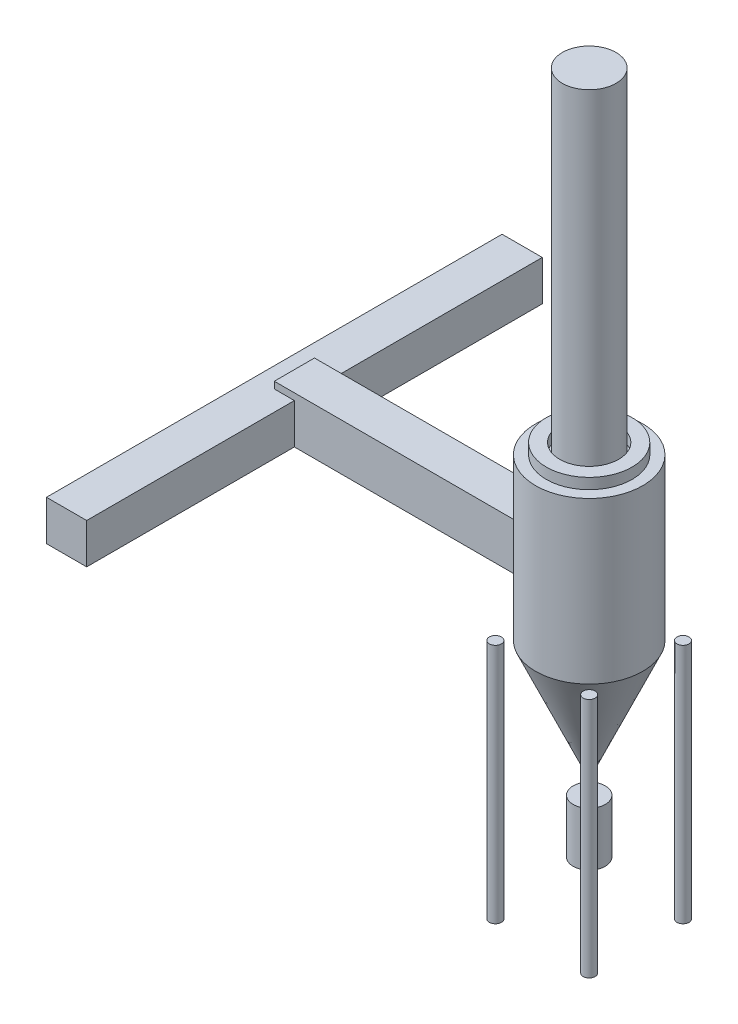
SolidWorks part; units mm, degrees
ref_plane "Front Plane" through (0, 0, 0) normal (0, 0, 1) x (1, 0, 0)
ref_plane "Top Plane" through (0, 0, 0) normal (0, 1, 0) x (1, 0, 0)
ref_plane "Right Plane" through (0, 0, 0) normal (1, 0, 0) x (0, 0, -1)
other "Configuration Table"
sketch "Sketch1" plane through (0, 0, 0) normal (0, 1, 0) x (1, 0, 0)
  circle A0 centre (1850, 5150) radius 45
extrude "Boss-Extrude1" add sketch "Sketch1" along normal blind 1800
sketch "Sketch2" plane through (0, 0, 0) normal (0, 1, 0) x (1, 0, 0)
  circle A0 centre (2550, 5150) radius 45
extrude "Boss-Extrude2" add sketch "Sketch2" along normal blind 1800
sketch "Sketch3" plane through (0, 0, 0) normal (0, 1, 0) x (1, 0, 0)
  circle A0 centre (1850, 5850) radius 45
extrude "Boss-Extrude3" add sketch "Sketch3" along normal blind 1800
sketch "Sketch4" plane through (0, 0, 0) normal (0, 1, 0) x (1, 0, 0)
  circle A0 centre (2550, 5850) radius 45
extrude "Boss-Extrude4" add sketch "Sketch4" along normal blind 1800
sketch "Sketch5" plane through (0, 0, 0) normal (0, 1, 0) x (1, 0, 0)
  circle A0 centre (2200, 5500) radius 120
extrude "Boss-Extrude5" add sketch "Sketch5" along normal blind 400 from offset 400
sketch "Sketch6" plane through (0, 0, 0) normal (0, 1, 0) x (1, 0, 0)
  circle A0 centre (2200, 5500) radius 400
extrude "Boss-Extrude6" add sketch "Sketch6" against normal blind 1000 draft 24 from offset 1800 flip side to cut
sketch "Sketch7" plane through (0, 0, 0) normal (0, 1, 0) x (1, 0, 0)
  circle A0 centre (2200, 5500) radius 400
extrude "Boss-Extrude7" add sketch "Sketch7" along normal blind 1200 from offset 1800
sketch "Sketch8" plane through (0, 0, 0) normal (0, 1, 0) x (1, 0, 0)
  circle A0 centre (2200, 5500) radius 200
extrude "Boss-Extrude8" add sketch "Sketch8" along normal blind 2500 from offset 3000
sketch "Sketch9" plane through (0, 0, 0) normal (0, 1, 0) x (1, 0, 0)
  circle A0 centre (2200, 5500) radius 320
  circle A1 centre (2200, 5500) radius 220
extrude "Boss-Extrude9" add sketch "Sketch9" along normal blind 80 from offset 3000
sketch "Sketch10" plane through (0, 0, 0) normal (0, 1, 0) x (1, 0, 0)
  line L1 (-150, 3800) -> (150, 3800)
  line L2 (-150, 3800) -> (-150, 7200)
  line L3 (-150, 7200) -> (150, 7200)
  line L4 (150, 3800) -> (150, 7200)
extrude "Boss-Extrude10" add sketch "Sketch10" along normal blind 300 from offset 2100
sketch "Sketch11" plane through (0, 0, 0) normal (0, 1, 0) x (1, 0, 0)
  line L1 (0, 5350) -> (1800, 5350)
  line L2 (0, 5350) -> (0, 5650)
  line L3 (0, 5650) -> (1800, 5650)
  line L4 (1800, 5350) -> (1800, 5650)
extrude "Boss-Extrude11" add sketch "Sketch11" along normal blind 350 from offset 2100
